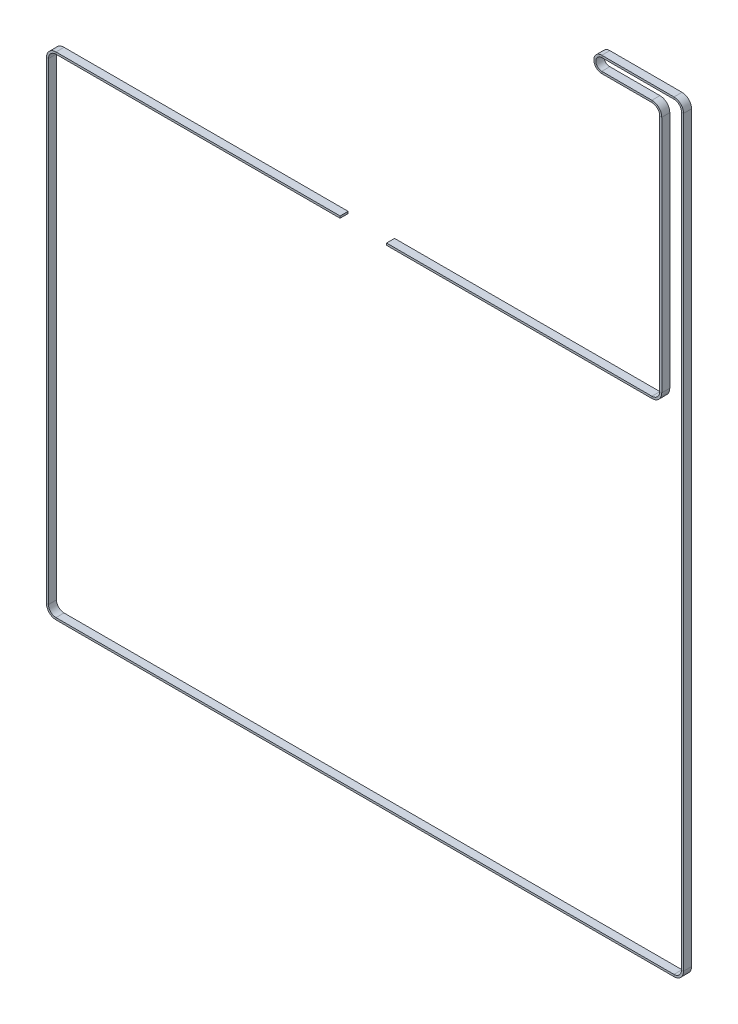
SolidWorks part; units mm, degrees
ref_plane "Front" through (0, 0, 0) normal (0, 0, 1) x (1, 0, 0)
ref_plane "Top" through (0, 0, 0) normal (0, 1, 0) x (1, 0, 0)
ref_plane "Right" through (0, 0, 0) normal (1, 0, 0) x (0, 0, -1)
sketch "Sketch1" plane through (0, 0, 0) normal (0, 0, 1) x (1, 0, 0)
  line L0 (377.3122, -142.2854) -> (431.3122, -142.2854)
  line L1 (377.3122, -152.6854) -> (414.8122, -152.6854)
  line L2 (421.4122, -159.2854) -> (421.4122, -337.7047)
  line L3 (437.6872, -148.6604) -> (437.6872, -703.9854)
  line L4 (-37.0628, -703.9854) -> (-37.0628, -350.5297)
  line L5 (431.3122, -710.3604) -> (-30.6878, -710.3604)
  line L6 (-30.6878, -344.1547) -> (181.7028, -344.1547)
  line L8 (216.4028, -344.2047) -> (216.4028, -347.7047) construction
  line L9 (414.8122, -344.3047) -> (216.4028, -344.3047)
  line L11 (181.7028, -344.2047) -> (181.7028, -347.7047) construction
  circle A0 centre (414.8122, -159.2854) radius 6.6 construction
  circle A1 centre (431.3122, -148.6604) radius 6.375 construction
  circle A2 centre (377.3122, -147.4854) radius 5.2 construction
  arc A3 (431.3122, -142.2854) -> (437.6872, -148.6604) centre (431.3122, -148.6604) cw
  arc A4 (377.3122, -152.6854) -> (377.3122, -142.2854) centre (377.3122, -147.4854) cw
  arc A5 (414.8122, -152.6854) -> (421.4122, -159.2854) centre (414.8122, -159.2854) cw
  circle A6 centre (-30.6878, -703.9854) radius 6.375 construction
  arc A7 (-30.6878, -710.3604) -> (-37.0628, -703.9854) centre (-30.6878, -703.9854) cw
  circle A8 centre (431.3122, -148.6604) radius 9 construction
  circle A9 centre (414.8122, -159.2854) radius 9 construction
  circle A10 centre (-30.6878, -350.5297) radius 6.375 construction
  circle A11 centre (431.3122, -703.9854) radius 6.375 construction
  arc A12 (437.6872, -703.9854) -> (431.3122, -710.3604) centre (431.3122, -703.9854) cw
  arc A13 (-37.0628, -350.5297) -> (-30.6878, -344.1547) centre (-30.6878, -350.5297) cw
  circle A14 centre (414.8122, -337.7047) radius 6.6 construction
  arc A15 (421.4122, -337.7047) -> (414.8122, -344.3047) centre (414.8122, -337.7047) cw
  dimension "D1" = 12.75
ref_plane "Plane1" through (181.7028, -344.1547, 0) normal (1, 0, 0) x (0, 0, -1)
sketch "Sketch4" plane through (181.7028, -344.1547, 0) normal (1, 0, 0) x (0, 0, -1)
  line L0 (0, 195.4943) -> (0, -359.8307) construction
  line L1 (3, -0.75) -> (-3, -0.75)
  line L2 (3, -0.75) -> (3, 0.75)
  line L3 (3, 0.75) -> (-3, 0.75)
  line L4 (-3, -0.75) -> (-3, 0.75)
  line L5 (3, -0.75) -> (-3, 0.75) construction
  line L6 (3, 0.75) -> (-3, -0.75) construction
  line L7 (0, 0) -> (0, -12.75) construction
  point P0 (0, 0)
  dimension "D1" = 1.5
  dimension "D2" = 6
sweep "Sweep1" add profiles "Sketch4" path "Sketch1"
